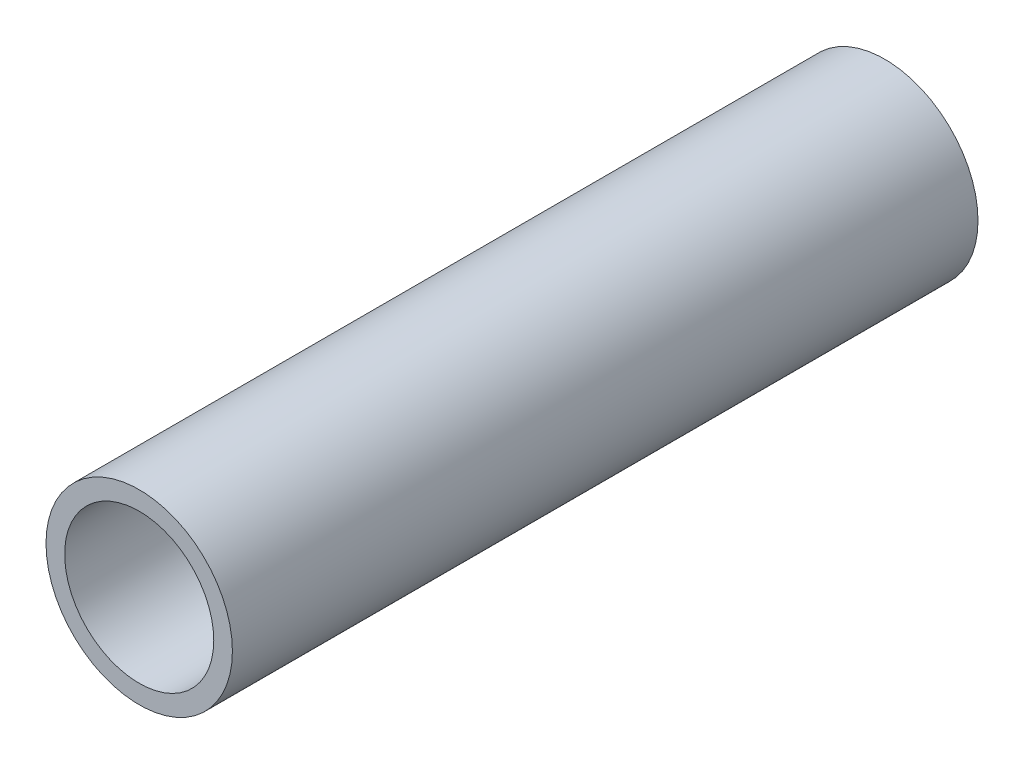
SolidWorks part; units mm, degrees
ref_plane "Front Plane" through (0, 0, 0) normal (0, 0, 1) x (1, 0, 0)
ref_plane "Top Plane" through (0, 0, 0) normal (0, 1, 0) x (1, 0, 0)
ref_plane "Right Plane" through (0, 0, 0) normal (1, 0, 0) x (0, 0, -1)
sketch "Sketch1" plane through (0, 0, 0) normal (0, 0, 1) x (1, 0, 0)
  circle A0 centre (0, 0) radius 5
  circle A1 centre (0, 0) radius 4
  dimension "D1" = 8
  dimension "D2" = 10
extrude "Boss-Extrude1" add sketch "Sketch1" along normal blind 40
